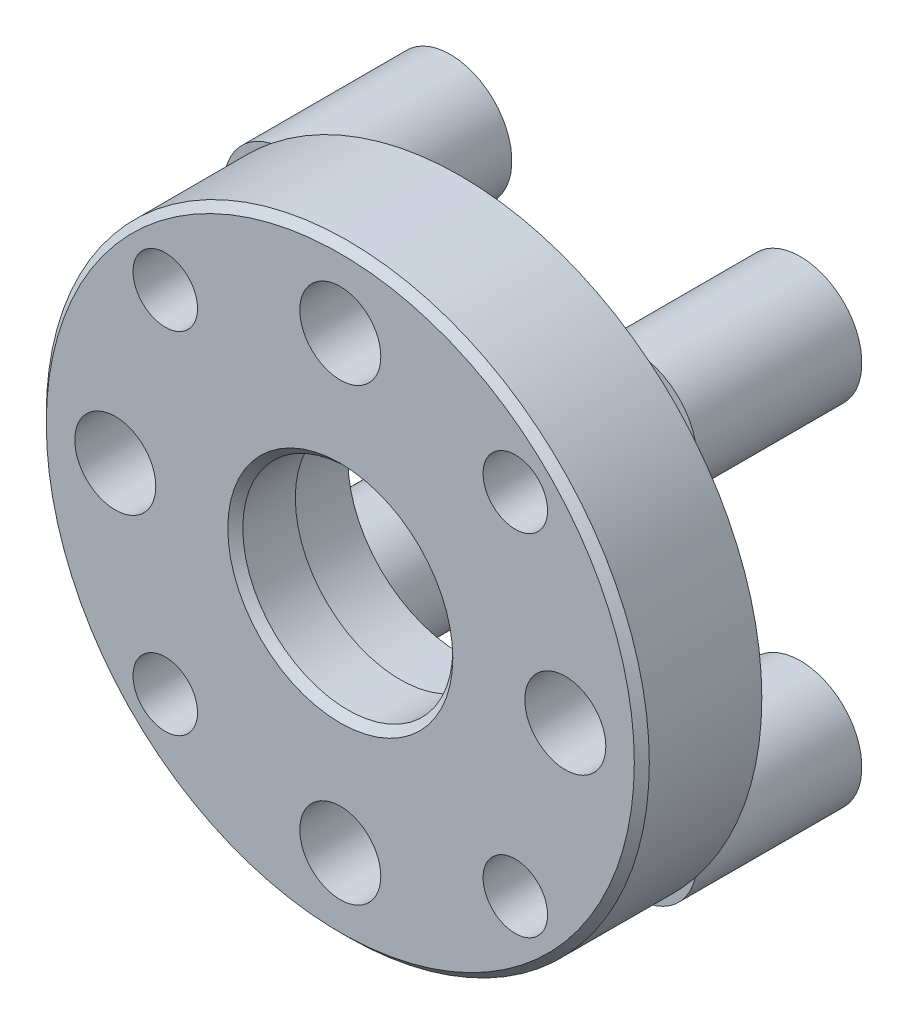
SolidWorks part; units mm, degrees
material "ABS"
ref_plane "Front Plane" through (0, 0, 0) normal (0, 0, 1) x (1, 0, 0)
ref_plane "Top Plane" through (0, 0, 0) normal (0, 1, 0) x (1, 0, 0)
ref_plane "Right Plane" through (0, 0, 0) normal (1, 0, 0) x (0, 0, -1)
ref_plane "Output Plane" through (0, 0, 25.2347) normal (0, 0, -1) x (-1, 0, 0)
sketch "CYC Output Sketch" plane through (0, 0, 25.2347) normal (0, 0, 1) x (1, 0, 0)
  line L1 (11.6673, 11.6673) -> (-11.6673, 11.6673) construction
  line L2 (-11.6673, 11.6673) -> (-11.6673, -11.6673) construction
  line L3 (-11.6673, -11.6673) -> (11.6673, -11.6673) construction
  line L4 (11.6673, -11.6673) -> (11.6673, 11.6673) construction
  circle A0 centre (0, 0) radius 16.5 construction
sketch "Sketch3" plane through (0, 0, 25.2347) normal (0, 0, -1) x (-1, 0, 0)
  circle A0 centre (-11.6673, 11.6673) radius 4
  circle A1 centre (11.6673, 11.6673) radius 4
  circle A2 centre (11.6673, -11.6673) radius 4
  circle A3 centre (-11.6673, -11.6673) radius 4
  dimension "D1" = 8
extrude "Boss-Extrude1" add sketch "Sketch3" along normal blind 11
sketch "Sketch6" plane through (0, 0, 25.2347) normal (0, 0, 1) x (1, 0, 0)
  arc A0 (10.7357, 16.9928) -> (-16.9928, 10.7357) centre (0, 0) ccw
  arc A18 (16.9928, -10.7357) -> (10.7357, 16.9928) centre (0, 0) ccw
  arc A19 (-10.7357, -16.9928) -> (16.9928, -10.7357) centre (0, 0) ccw
  arc A20 (-16.9928, 10.7357) -> (-10.7357, -16.9928) centre (0, 0) ccw
  circle A23 centre (0, 0) radius 7.5
  dimension "D2" = 40.2
  dimension "D1" = 15
extrude "Boss-Extrude6" add sketch "Sketch6" along normal blind 8 contours A23 | A0 A20 A19 A18
sketch "Sketch8" plane through (0, 0, 33.2347) normal (0, 0, 1) x (1, 0, 0)
  line L0 (0, 0) -> (11.6673, 11.6673) construction
  line L1 (0, 0) -> (16.5, 0) construction
  circle A0 centre (0, 0) radius 16.5 construction
  circle A1 centre (11.6673, 11.6673) radius 1.6
  circle A2 centre (11.6673, -11.6673) radius 1.6
  circle A3 centre (-11.6673, -11.6673) radius 1.6
  circle A4 centre (-11.6673, 11.6673) radius 1.6
  point P16 (0, 0)
  dimension "D1" = 33
  dimension "D2" = 45
  dimension "D3" = 3.2
  dimension "D4" = 4
extrude "Cut-Extrude1" cut sketch "Sketch8" against normal through all
sketch "Sketch9" plane through (0, 0, 14.2347) normal (0, 0, 1) x (1, 0, 0)
  circle A0 centre (11.6673, 11.6673) radius 3
  circle A1 centre (11.6673, -11.6673) radius 3
  circle A2 centre (-11.6673, -11.6673) radius 3
  circle A3 centre (-11.6673, 11.6673) radius 3
  point P12 (0, 0)
  dimension "D1" = 6
  dimension "D2" = 4
extrude "Cut-Extrude2" cut sketch "Sketch9" along normal blind 3 from surface at 0 starting at face at (13.2673, 11.6673, 14.2347)
sketch "Sketch10" plane through (0, 0, 14.2347) normal (0, 0, -1) x (-1, 0, 0)
  circle A0 centre (11.6673, 11.6673) radius 4.1
  circle A1 centre (11.6673, 11.6673) radius 4
  circle A2 centre (11.6673, -11.6673) radius 4
  circle A3 centre (11.6673, -11.6673) radius 4.1
  circle A4 centre (-11.6673, -11.6673) radius 4
  circle A5 centre (-11.6673, -11.6673) radius 4.1
  circle A6 centre (-11.6673, 11.6673) radius 4
  circle A7 centre (-11.6673, 11.6673) radius 4.1
  point P16 (0, 0)
  dimension "D1" = 8
  dimension "D2" = 8.2
  dimension "D3" = 4
extrude "Boss-Extrude8" add sketch "Sketch10" against normal blind 11
sketch "Sketch11" plane through (0, 0, 33.2347) normal (0, 0, 1) x (1, 0, 0)
  line L0 (0, 0) -> (0, 15) construction
  circle A0 centre (0, 15) radius 2.7
  circle A1 centre (15, 0) radius 2.7
  circle A2 centre (0, -15) radius 2.7
  circle A3 centre (-15, 0) radius 2.7
  circle A4 centre (-11.6673, 11.6673) radius 2.15
  circle A5 centre (11.6673, 11.6673) radius 2.15
  circle A6 centre (11.6673, -11.6673) radius 2.15
  circle A7 centre (-11.6673, -11.6673) radius 2.15
  point P13 (0, 0)
  dimension "D2" = 5.4
  dimension "D4" = 4.3
  dimension "D1" = 15
  dimension "D3" = 4
extrude "Cut-Extrude3" cut sketch "Sketch11" against normal blind 8
sketch "Sketch12" plane through (0, 0, 33.2347) normal (0, 0, 1) x (1, 0, 0)
  circle A0 centre (0, 0) radius 7.5
  circle A1 centre (0, 0) radius 7
  dimension "D1" = 15
  dimension "D2" = 14
extrude "Boss-Extrude9" add sketch "Sketch12" against normal blind 4
chamfer "Chamfer1" distance 0.5 angle 45 2 edges at (7, 0, 33.2347) (20.1, 0, 33.2347)
equation "\"RingPinShaft\"= 5.05"
equation "\"CenterBearingOut\"=32.00"
equation "\"RingPostIn\"=5.15"
equation "\"CamBearingOut\"=15.1"
equation "\"DiskOutputShaft\"=10.1"
equation "\"CenterShaft\"=25.2"
equation "\"Eccentricity\"=2"
equation "\"CycCamShaft\"=10.05"
equation "\"D2@Sketch6\"=\"OutputBearing\""
equation "\"OutputBearing\"=40.2"
